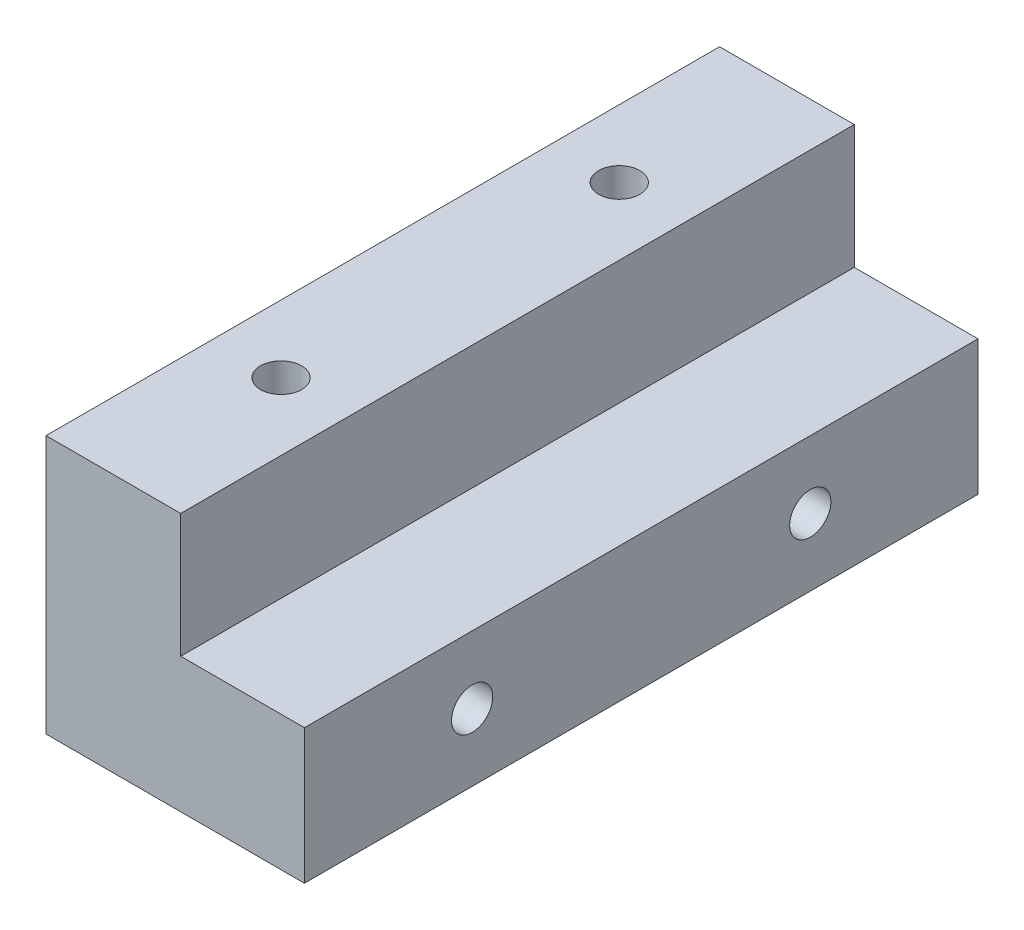
SolidWorks part; units mm, degrees
ref_plane "前基準面" through (0, 0, 0) normal (0, 0, 1) x (1, 0, 0)
ref_plane "上基準面" through (0, 0, 0) normal (0, 1, 0) x (1, 0, 0)
ref_plane "右基準面" through (0, 0, 0) normal (1, 0, 0) x (0, 0, -1)
sketch "草圖1" plane through (0, 0, 0) normal (0, 0, 1) x (1, 0, 0)
  line L0 (0, 9.4) -> (0, 0)
  line L1 (0, 0) -> (9.4, 0)
  line L2 (9.4, 0) -> (9.4, 4.9)
  line L3 (9.4, 4.9) -> (4.9, 4.9)
  line L4 (4.9, 4.9) -> (4.9, 9.4)
  line L5 (4.9, 9.4) -> (0, 9.4)
  dimension "D1" = 4.5
  dimension "D2" = 4.5
  dimension "D3" = 4.9
  dimension "D4" = 4.9
extrude "填料-伸長1" add sketch "草圖1" along normal blind 24.5
sketch "草圖2" plane through (9.4, 0, 0) normal (1, 0, 0) x (0, 0, -1)
  line L0 (0, 2.45) -> (-24.5, 2.45) construction
  line L1 (0, 0) -> (0, 4.9) construction
  line L2 (-24.5, 0) -> (-24.5, 4.9) construction
  circle A0 centre (-6.1, 2.45) radius 0.75
  circle A1 centre (-18.4, 2.45) radius 0.75
  dimension "D3" = 1.5
  dimension "D4" = 1.5
  dimension "D1" = 6.1
  dimension "D2" = 6.1
extrude "除料-伸長1" cut sketch "草圖2" against normal blind 5
sketch "草圖3" plane through (0, 9.4, 0) normal (0, 1, 0) x (1, 0, 0)
  line L0 (2.45, 0) -> (2.45, -24.5) construction
  line L1 (4.9, 0) -> (0, 0) construction
  line L2 (4.9, -24.5) -> (0, -24.5) construction
  circle A0 centre (2.45, -6.1) radius 0.75
  circle A1 centre (2.45, -18.4) radius 0.75
  dimension "D1" = 1.5
  dimension "D2" = 1.5
  dimension "D3" = 6.1
  dimension "D4" = 6.1
extrude "除料-伸長2" cut sketch "草圖3" against normal blind 5
